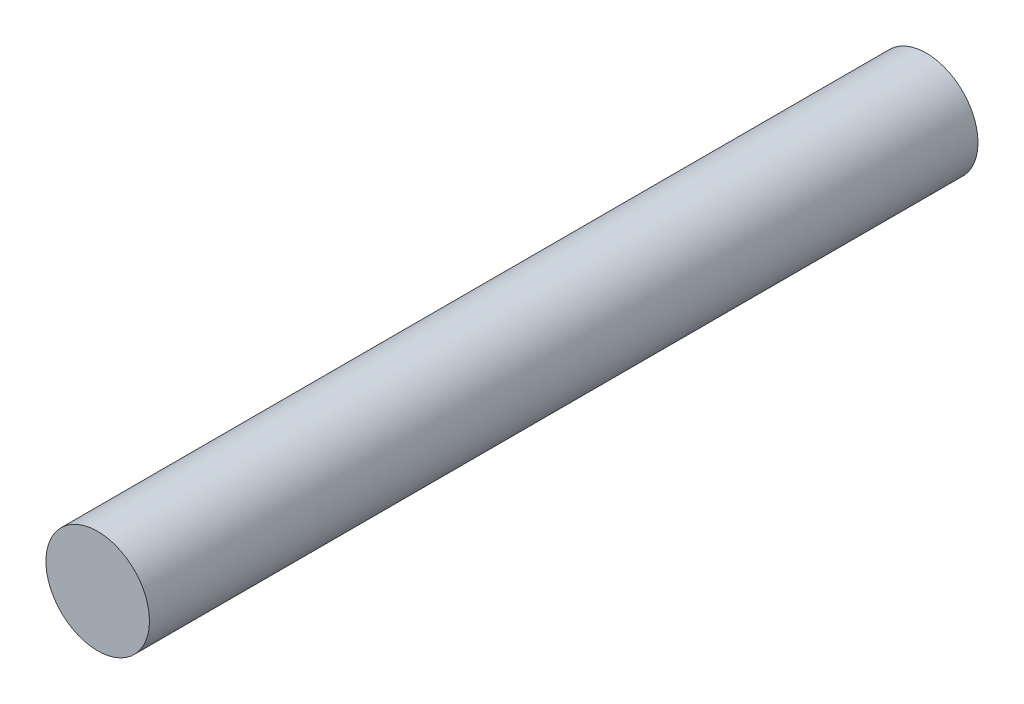
SolidWorks part; units mm, degrees
ref_plane "前视基准面" through (0, 0, 0) normal (0, 0, 1) x (1, 0, 0)
ref_plane "上视基准面" through (0, 0, 0) normal (0, 1, 0) x (1, 0, 0)
ref_plane "右视基准面" through (0, 0, 0) normal (1, 0, 0) x (0, 0, -1)
sketch "草图2" plane through (0, 0, 0) normal (0, 0, 1) x (1, 0, 0)
  circle A0 centre (0, 0) radius 0.25
  dimension "D1" = 0.5
extrude "凸台-拉伸1" add sketch "草图2" along normal blind 4
